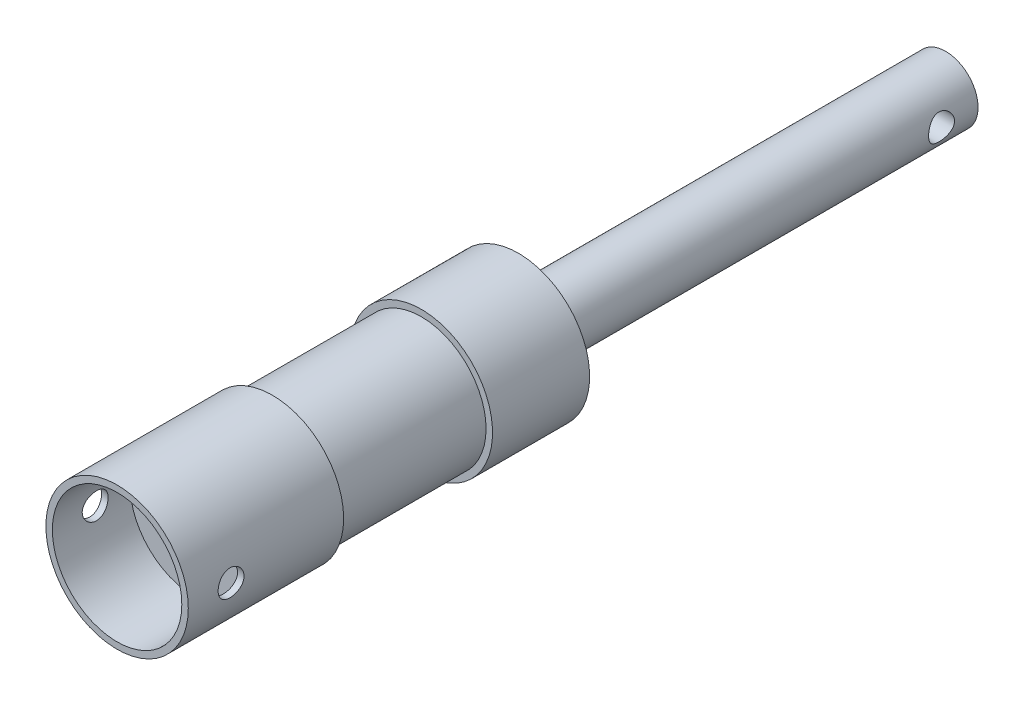
SolidWorks part; units mm, degrees
ref_plane "Front Plane" through (0, 0, 0) normal (0, 0, 1) x (1, 0, 0)
ref_plane "Top Plane" through (0, 0, 0) normal (0, 1, 0) x (1, 0, 0)
ref_plane "Right Plane" through (0, 0, 0) normal (1, 0, 0) x (0, 0, -1)
sketch "Sketch1" plane through (0, 0, 0) normal (0, 0, 1) x (1, 0, 0)
  circle A0 centre (0, 0) radius 10
extrude "Boss-Extrude1" add sketch "Sketch1" against normal blind 50 contours A0
sketch "Sketch2" plane through (0, 0, -50) normal (0, 0, -1) x (-1, 0, 0)
  circle A0 centre (0, 0) radius 10
extrude "Extrude-Thin1" add sketch "Sketch2" against normal blind 15 thin contours A0
sketch "Sketch3" plane through (0, 0, -50) normal (0, 0, -1) x (-1, 0, 0)
  circle A0 centre (0, 0) radius 5
extrude "Boss-Extrude2" add sketch "Sketch3" along normal blind 66 contours A0
sketch "Sketch4" plane through (0, 0, 0) normal (1, 0, 0) x (0, 0, -1)
  circle A0 centre (110.3602, 0) radius 2
extrude "Cut-Extrude3" cut sketch "Sketch4" against normal through all both and the other way through all contours A0
sketch "Sketch5" plane through (0, 0, 0) normal (0, 0, 1) x (1, 0, 0)
  circle A0 centre (0, 0) radius 10
extrude "Extrude-Thin2" add sketch "Sketch5" against normal blind 12 and the other way blind 12 thin contours A0
sketch "Sketch7" plane through (0, 0, 0) normal (1, 0, 0) x (0, 0, -1)
  circle A0 centre (-5.3862, 0) radius 2
extrude "Cut-Extrude4" cut sketch "Sketch7" against normal through all both and the other way through all contours A0
